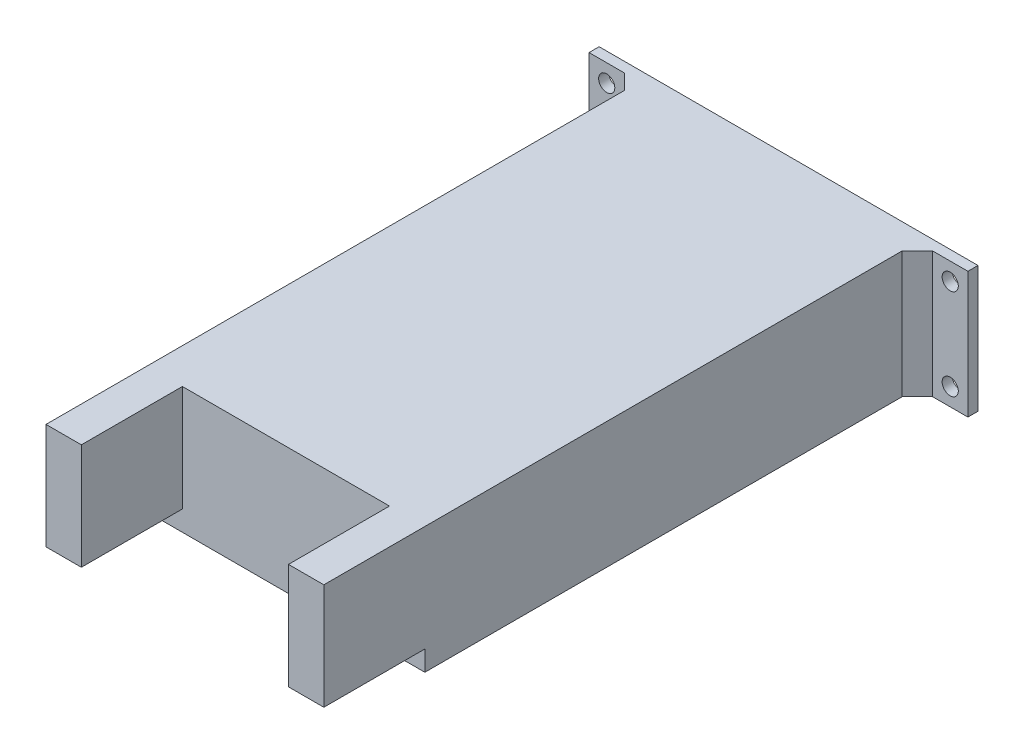
SolidWorks part; units mm, degrees
ref_plane "正面" through (0, 0, 0) normal (0, 0, 1) x (1, 0, 0)
ref_plane "平面" through (0, 0, 0) normal (0, 1, 0) x (1, 0, 0)
ref_plane "右側面" through (0, 0, 0) normal (1, 0, 0) x (0, 0, -1)
sketch "ｽｹｯﾁ1" plane through (0, 0, 0) normal (0, 0, 1) x (1, 0, 0)
  line L1 (-12.7289, 5.1915) -> (42.2711, 5.1915)
  line L2 (-12.7289, 5.1915) -> (-12.7289, -19.8085)
  line L3 (-12.7289, -19.8085) -> (42.2711, -19.8085)
  line L4 (42.2711, 5.1915) -> (42.2711, -19.8085)
  dimension "D1" = 55
  dimension "D2" = 25
extrude "ﾎﾞｽ - 押し出し1" add sketch "ｽｹｯﾁ1" along normal blind 119.5
sketch "ｽｹｯﾁ3" plane through (42.2711, 0, 0) normal (1, 0, 0) x (0, 0, -1)
  line L0 (-119.5, -19.8085) -> (0, -19.8085) construction
  line L1 (0, 5.1915) -> (-2, 5.1915)
  line L2 (0, 5.1915) -> (0, -19.8085)
  line L3 (0, -19.8085) -> (-2, -19.8085)
  line L4 (-2, 5.1915) -> (-2, -19.8085)
  dimension "D2" = 2
extrude "ﾎﾞｽ - 押し出し2" add sketch "ｽｹｯﾁ3" along normal blind 10
sketch "ｽｹｯﾁ5" plane through (0, 5.1915, 0) normal (0, 1, 0) x (1, 0, 0)
  line L0 (42.2711, -5) -> (45.2711, -2)
  line L1 (42.2711, -119.5) -> (42.2711, -2) construction
  line L2 (52.2711, -2) -> (42.2711, -2) construction
  line L3 (45.2711, -2) -> (42.2711, -2)
  line L4 (42.2711, -2) -> (42.2711, -5)
  dimension "D1" = 3
extrude "ﾎﾞｽ - 押し出し3" add sketch "ｽｹｯﾁ5" against normal through all
sketch "ｽｹｯﾁ6" plane through (0, 0, 2) normal (0, 0, 1) x (1, 0, 0)
  line L0 (48.7711, 1.6915) -> (45.2711, 1.6915) construction
  line L1 (45.2711, -19.8085) -> (45.2711, 5.1915) construction
  line L2 (48.7711, 1.6915) -> (52.2711, 1.6915) construction
  line L3 (52.2711, 5.1915) -> (52.2711, -19.8085) construction
  line L4 (48.7711, -16.3085) -> (45.2711, -16.3085) construction
  line L5 (48.7711, -16.3085) -> (52.2711, -16.3085) construction
  line L6 (48.7711, -16.3085) -> (48.7711, -19.8085) construction
  line L7 (52.2711, -19.8085) -> (45.2711, -19.8085) construction
  line L8 (48.7711, 1.6915) -> (48.7711, 5.1915) construction
  line L9 (52.2711, 5.1915) -> (45.2711, 5.1915) construction
  circle A0 centre (48.7711, 1.6915) radius 1.6
  circle A1 centre (48.7711, -16.3085) radius 1.6
  dimension "D1" = 3.2
  dimension "D2" = 3.2
extrude "ｶｯﾄ - 押し出し2" cut sketch "ｽｹｯﾁ6" against normal through all
sketch "ｽｹｯﾁ7" plane through (-12.7289, 0, 0) normal (-1, 0, 0) x (0, 0, 1)
  line L0 (119.5, 5.1915) -> (0, 5.1915) construction
  line L1 (0, -19.8085) -> (2, -19.8085)
  line L2 (0, -19.8085) -> (0, 5.1915)
  line L3 (0, 5.1915) -> (2, 5.1915)
  line L4 (2, -19.8085) -> (2, 5.1915)
  dimension "D1" = 2
extrude "ﾎﾞｽ - 押し出し4" add sketch "ｽｹｯﾁ7" along normal blind 10
sketch "ｽｹｯﾁ8" plane through (0, -19.8085, 0) normal (0, -1, 0) x (1, 0, 0)
  line L0 (-12.7289, 5) -> (-15.7289, 2)
  line L1 (-12.7289, 119.5) -> (-12.7289, 2) construction
  line L2 (-22.7289, 2) -> (-12.7289, 2) construction
  line L3 (-15.7289, 2) -> (-12.7289, 2)
  line L4 (-12.7289, 2) -> (-12.7289, 5)
  dimension "D1" = 3
extrude "ﾎﾞｽ - 押し出し5" add sketch "ｽｹｯﾁ8" against normal through all
sketch "ｽｹｯﾁ9" plane through (0, 0, 2) normal (0, 0, 1) x (1, 0, 0)
  line L0 (-19.2289, 1.6915) -> (-15.7289, 1.6915) construction
  line L1 (-15.7289, 5.1915) -> (-15.7289, -19.8085) construction
  line L2 (-19.2289, 1.6915) -> (-22.7289, 1.6915) construction
  line L3 (-22.7289, -19.8085) -> (-22.7289, 5.1915) construction
  line L4 (-19.2289, -16.3085) -> (-22.7289, -16.3085) construction
  line L5 (-19.2289, -16.3085) -> (-15.7289, -16.3085) construction
  line L6 (-19.2289, 1.6915) -> (-19.2289, 5.1915) construction
  line L7 (-22.7289, 5.1915) -> (-15.7289, 5.1915) construction
  line L8 (-19.2289, -16.3085) -> (-19.2289, -19.8085) construction
  line L9 (-22.7289, -19.8085) -> (-15.7289, -19.8085) construction
  circle A0 centre (-19.2289, -16.3085) radius 1.6
  circle A1 centre (-19.2289, 1.6915) radius 1.6
  dimension "D1" = 3.2
  dimension "D2" = 3.2
extrude "ｶｯﾄ - 押し出し3" cut sketch "ｽｹｯﾁ9" against normal through all
sketch "ｽｹｯﾁ10" plane through (0, 0, 119.5) normal (0, 0, 1) x (1, 0, 0)
  line L0 (-12.7289, 5.1915) -> (-12.7289, -19.8085) construction
  line L1 (42.2711, -19.8085) -> (-12.7289, -19.8085)
  line L2 (42.2711, -19.8085) -> (42.2711, -15.8085)
  line L3 (42.2711, -15.8085) -> (-12.7289, -15.8085)
  line L4 (-12.7289, -19.8085) -> (-12.7289, -15.8085)
  dimension "D2" = 55
  dimension "D3" = 4
extrude "ｶｯﾄ - 押し出し4" cut sketch "ｽｹｯﾁ10" against normal blind 20 contours L1 L4 L3 L2
sketch "ｽｹｯﾁ12" plane through (0, 0, 119.5) normal (0, 0, 1) x (1, 0, 0)
  line L0 (42.2711, -15.8085) -> (-12.7289, -15.8085) construction
  line L1 (35.2711, -15.8085) -> (-5.7289, -15.8085)
  line L2 (35.2711, -15.8085) -> (35.2711, 5.1915)
  line L3 (35.2711, 5.1915) -> (-5.7289, 5.1915)
  line L4 (-5.7289, -15.8085) -> (-5.7289, 5.1915)
  line L5 (42.2711, 5.1915) -> (-12.7289, 5.1915) construction
  line L6 (35.2711, -15.8085) -> (42.2711, -15.8085) construction
  line L7 (-12.7289, -15.8085) -> (-5.7289, -15.8085) construction
  dimension "D1" = 21
  dimension "D2" = 41
extrude "ｶｯﾄ - 押し出し5" cut sketch "ｽｹｯﾁ12" against normal blind 20
sketch "ｽｹｯﾁ13" plane through (0, -15.8085, 0) normal (0, -1, 0) x (1, 0, 0)
  line L2 (35.2711, 99.5) -> (35.2711, 119.5) construction
  line L3 (39.2711, 104.5) -> (35.2711, 104.5) construction
  line L4 (39.2711, 114.5) -> (35.2711, 114.5) construction
  line L5 (39.2711, 114.5) -> (39.2711, 119.5) construction
  line L6 (42.2711, 119.5) -> (35.2711, 119.5) construction
  line L7 (39.2711, 104.5) -> (39.2711, 99.5) construction
  line L8 (42.2711, 99.5) -> (35.2711, 99.5) construction
  circle A0 centre (39.2711, 104.5) radius 1.4
  circle A1 centre (39.2711, 114.5) radius 1.4
  dimension "D1" = 10
  dimension "D4" = 2.8
  dimension "D3" = 4
extrude "ｶｯﾄ - 押し出し6" cut sketch "ｽｹｯﾁ13" against normal blind 10
sketch "ｽｹｯﾁ15" plane through (0, -15.8085, 0) normal (0, -1, 0) x (-1, 0, 0)
  line L3 (5.7289, -99.5) -> (5.7289, -119.5) construction
  line L4 (9.7289, -114.5) -> (5.7289, -114.5) construction
  line L5 (9.7289, -104.5) -> (5.7289, -104.5) construction
  line L6 (9.7289, -114.5) -> (9.7289, -119.5) construction
  line L7 (5.7289, -119.5) -> (12.7289, -119.5) construction
  line L8 (9.7289, -104.5) -> (9.7289, -99.5) construction
  line L9 (5.7289, -99.5) -> (12.7289, -99.5) construction
  circle A0 centre (9.7289, -104.5) radius 1.4
  circle A1 centre (9.7289, -114.5) radius 1.4
  dimension "D1" = 10
  dimension "D4" = 2.8
  dimension "D3" = 4
extrude "ｶｯﾄ - 押し出し7" cut sketch "ｽｹｯﾁ15" against normal blind 10
